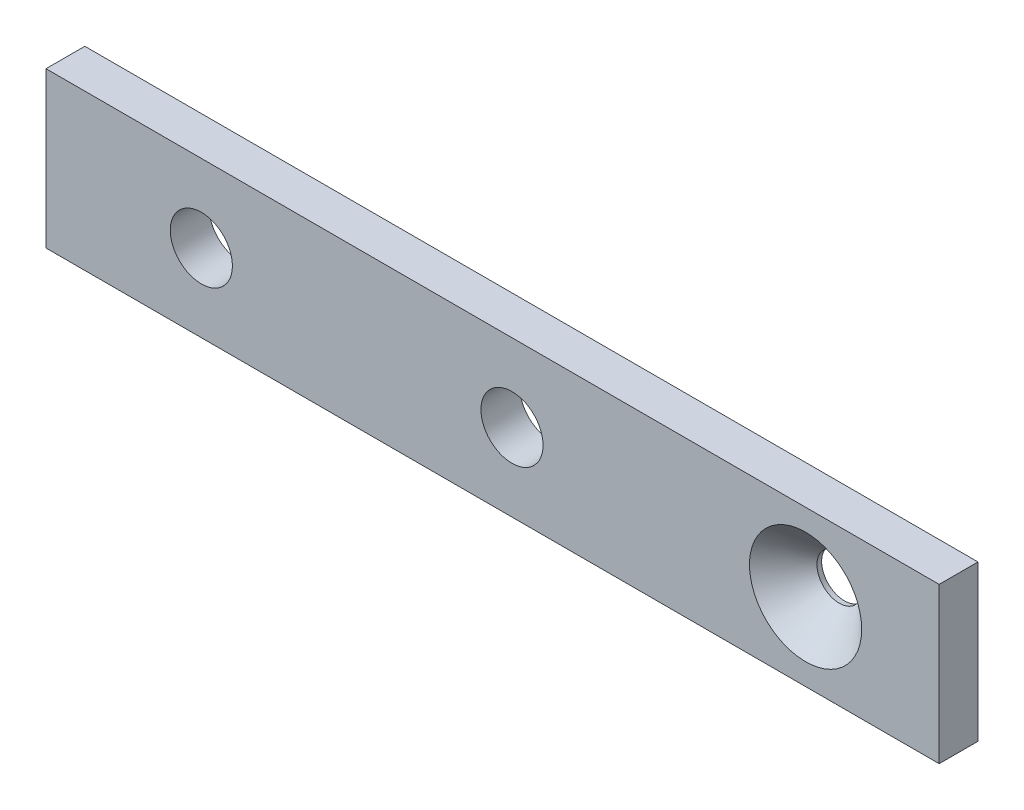
SolidWorks part; units mm, degrees
ref_plane "Front Plane" through (0, 0, 0) normal (0, 0, 1) x (1, 0, 0)
ref_plane "Top Plane" through (0, 0, 0) normal (0, 1, 0) x (1, 0, 0)
ref_plane "Right Plane" through (0, 0, 0) normal (1, 0, 0) x (0, 0, -1)
sketch "Sketch1" plane through (0, 0, 0) normal (0, 0, 1) x (1, 0, 0)
  line L0 (-12.7, 0) -> (12.7, 0) construction
  line L2 (-25.4, -6.35) -> (25.4, -6.35)
  line L3 (-25.4, -6.35) -> (-25.4, 6.35)
  line L4 (-25.4, 6.35) -> (25.4, 6.35)
  line L6 (-25.4, -6.35) -> (25.4, 6.35) construction
  line L7 (-25.4, 6.35) -> (25.4, -6.35) construction
  line L8 (25.4, 6.35) -> (47.625, 6.35)
  line L10 (25.4, -6.35) -> (47.625, -6.35)
  line L11 (47.625, 6.35) -> (47.625, -6.35)
  line L12 (25.4, 6.35) -> (47.625, -6.35) construction
  line L13 (25.4, -6.35) -> (47.625, 6.35) construction
  circle A0 centre (-12.7, 0) radius 2.54
  circle A1 centre (12.7, 0) radius 2.54
  point P4 (0, 0)
  point P6 (0, 0)
  point P15 (36.5125, 0)
  dimension "D2" = 5.08
  dimension "D3" = 50.8
  dimension "D1" = 25.4
  dimension "D4" = 22.225
  dimension "D5" = 6.35
extrude "Boss-Extrude1" add sketch "Sketch1" along normal blind 3.175 contours L11 L8 L4 L3 L2 L10 A1 A0
sketch "Sketch3" plane through (0, 0, 3.175) normal (0, 0, 1) x (1, 0, 0)
  line L0 (47.625, 6.35) -> (47.625, -6.35) construction
  circle A0 centre (36.703, 0) radius 1.5875
  dimension "D1" = 10.922
  dimension "D2" = 3.175
  dimension "D3" = 6.35
extrude "Cut-Extrude1" cut sketch "Sketch3" against normal through all draft 5 draft outward yes
chamfer "Chamfer1" distance 3 angle 45 1 edges at (38.2905, 0, 3.175)
